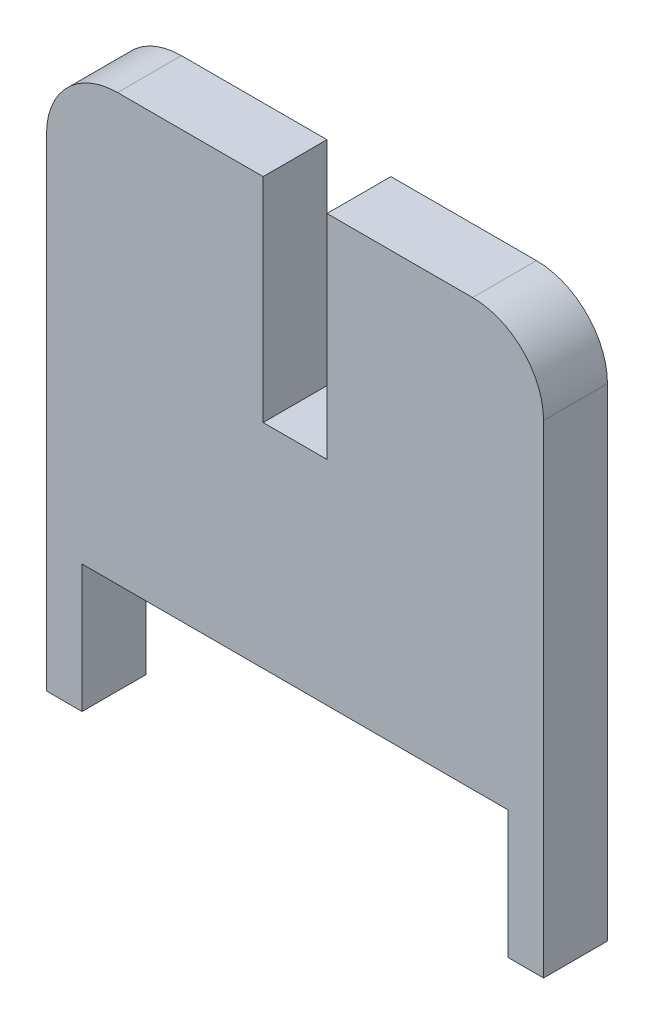
SolidWorks part; units mm, degrees
material "Balsa"
ref_plane "Front Plane" through (0, 0, 0) normal (0, 0, 1) x (1, 0, 0)
ref_plane "Top Plane" through (0, 0, 0) normal (0, 1, 0) x (1, 0, 0)
ref_plane "Right Plane" through (0, 0, 0) normal (1, 0, 0) x (0, 0, -1)
sketch "Sketch1" plane through (0, 0, 0) normal (0, 0, 1) x (1, 0, 0)
  line L1 (17.5, -15) -> (-17.5, -15)
  line L2 (17.5, -15) -> (17.5, 15)
  line L3 (17.5, 15) -> (-17.5, 15)
  line L4 (-17.5, -15) -> (-17.5, 15)
  line L5 (17.5, -15) -> (-17.5, 15) construction
  line L6 (17.5, 15) -> (-17.5, -15) construction
  line L7 (-17.5, -15) -> (-15, -15)
  line L8 (-17.5, -15) -> (-17.5, -24)
  line L9 (-17.5, -24) -> (-15, -24)
  line L10 (-15, -15) -> (-15, -24)
  line L11 (17.5, -15) -> (15, -15)
  line L12 (17.5, -15) -> (17.5, -24)
  line L13 (17.5, -24) -> (15, -24)
  line L14 (15, -15) -> (15, -24)
  point P0 (0, 0)
  dimension "D1" = 30
  dimension "D2" = 35
  dimension "D3" = 9
  dimension "D4" = 2.5
  dimension "D5" = 2.5
extrude "Boss-Extrude1" add sketch "Sketch1" along normal blind 4.5 contours L4 L1 L2 L3 | L10 L1 L8 L9 | L1 L14 L13 L12
fillet "Fillet1" radius 5 2 edges at (-17.5, 15, 2.25) (17.5, 15, 2.25)
sketch "Sketch2" plane through (0, 0, 4.5) normal (0, 0, 1) x (1, 0, 0)
  line L0 (12.5, 15) -> (-12.5, 15) construction
  line L1 (2.25, -15) -> (-2.25, -15)
  line L2 (2.25, -15) -> (2.25, 15)
  line L3 (2.25, 15) -> (-2.25, 15)
  line L4 (-2.25, -15) -> (-2.25, 15)
  line L5 (2.25, -15) -> (-2.25, 15) construction
  line L6 (2.25, 15) -> (-2.25, -15) construction
  line L7 (2.25, 0) -> (-2.25, 0)
  point P0 (0, 0)
  line M2 (12.5, 15) -> (-12.5, 15)
  dimension "D1" = 4.5
extrude "Cut-Extrude1" cut sketch "Sketch2" against normal blind 4.5 contours L7 L2 L4 M2
